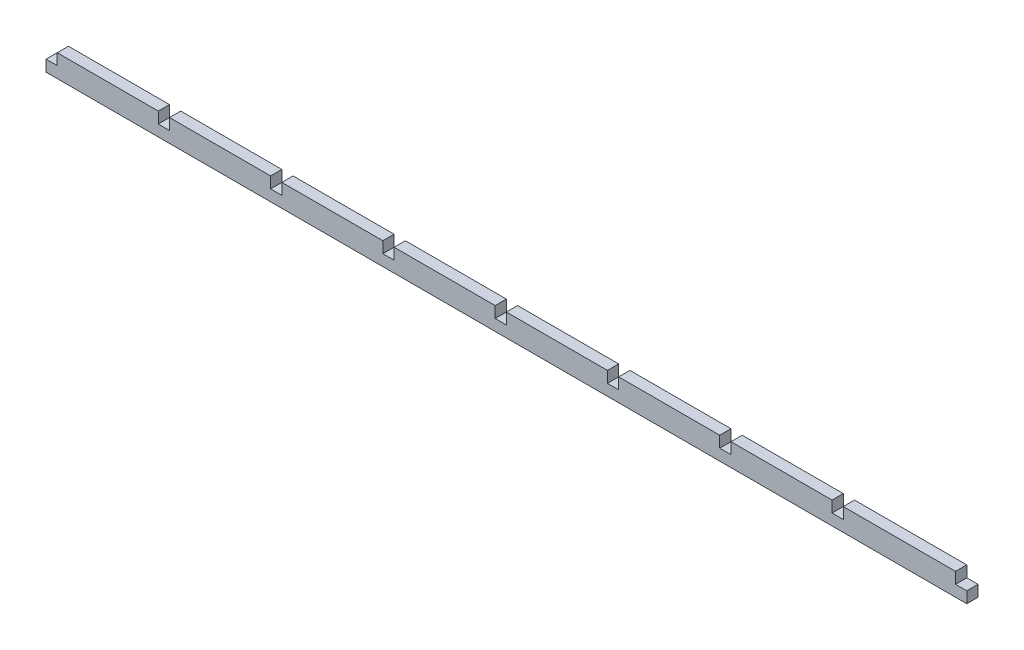
SolidWorks part; units mm, degrees
ref_plane "Front Plane" through (0, 0, 0) normal (0, 0, 1) x (1, 0, 0)
ref_plane "Top Plane" through (0, 0, 0) normal (0, 1, 0) x (1, 0, 0)
ref_plane "Right Plane" through (0, 0, 0) normal (1, 0, 0) x (0, 0, -1)
sketch "Sketch1" plane through (0, 0, 0) normal (0, 0, 1) x (1, 0, 0)
  line L0 (-39.1131, 50.2449) -> (-39.1131, 59.2865) construction
  line L1 (-159.1131, 58.7617) -> (-132.1131, 58.7617)
  line L2 (-159.1131, 58.7617) -> (-159.1131, 55.7617)
  line L4 (80.8869, 58.7617) -> (80.8869, 55.7617)
  line L5 (-159.1131, 55.7617) -> (-162.1131, 55.7617)
  line L7 (-159.1131, 52.7617) -> (-162.1131, 52.7617)
  line L8 (-162.1131, 55.7617) -> (-162.1131, 52.7617)
  line L10 (-132.1131, 58.7617) -> (-132.1131, 55.7617)
  line L11 (-132.1131, 55.7617) -> (-129.1131, 55.7617)
  line L12 (-129.1131, 58.7617) -> (-129.1131, 55.7617)
  line L13 (80.8869, 52.7617) -> (83.8869, 52.7617)
  line L14 (83.8869, 55.7617) -> (83.8869, 52.7617)
  line L15 (80.8869, 55.7617) -> (83.8869, 55.7617)
  line L17 (-102.1131, 58.7617) -> (-102.1131, 55.7617)
  line L19 (-99.1131, 58.7617) -> (-99.1131, 55.7617)
  line L20 (-102.1131, 55.7617) -> (-99.1131, 55.7617)
  line L21 (-72.1131, 58.7617) -> (-72.1131, 55.7617)
  line L23 (-69.1131, 58.7617) -> (-69.1131, 55.7617)
  line L24 (-72.1131, 55.7617) -> (-69.1131, 55.7617)
  line L25 (-42.1131, 58.7617) -> (-42.1131, 55.7617)
  line L27 (-39.1131, 58.7617) -> (-39.1131, 55.7617)
  line L28 (-42.1131, 55.7617) -> (-39.1131, 55.7617)
  line L29 (-12.1131, 58.7617) -> (-12.1131, 55.7617)
  line L31 (-9.1131, 58.7617) -> (-9.1131, 55.7617)
  line L32 (-12.1131, 55.7617) -> (-9.1131, 55.7617)
  line L33 (17.8869, 58.7617) -> (17.8869, 55.7617)
  line L35 (20.8869, 58.7617) -> (20.8869, 55.7617)
  line L36 (17.8869, 55.7617) -> (20.8869, 55.7617)
  line L37 (47.8869, 58.7617) -> (47.8869, 55.7617)
  line L39 (50.8869, 58.7617) -> (50.8869, 55.7617)
  line L40 (47.8869, 55.7617) -> (50.8869, 55.7617)
  line L41 (-129.1131, 58.7617) -> (-102.1131, 58.7617)
  line L42 (-99.1131, 58.7617) -> (-72.1131, 58.7617)
  line L43 (-69.1131, 58.7617) -> (-42.1131, 58.7617)
  line L44 (-39.1131, 58.7617) -> (-12.1131, 58.7617)
  line L45 (-9.1131, 58.7617) -> (17.8869, 58.7617)
  line L46 (50.8869, 58.7617) -> (80.8869, 58.7617)
  line L49 (20.8869, 58.7617) -> (47.8869, 58.7617)
  line L50 (-159.1131, 52.7617) -> (80.8869, 52.7617)
  point P1 (0, 0)
  point P2 (0, 0)
  dimension "D1" = 240
  dimension "D2" = 3
  dimension "D3" = 3
  dimension "D4" = 3
  dimension "D5" = 3
  dimension "D6" = 27
  dimension "D7" = 3
  dimension "D8" = 3
  dimension "D10" = 27
  dimension "D9" = 7
extrude "Boss-Extrude1" add sketch "Sketch1" along normal blind 3
equation "\"2ю7\"=2.7"
